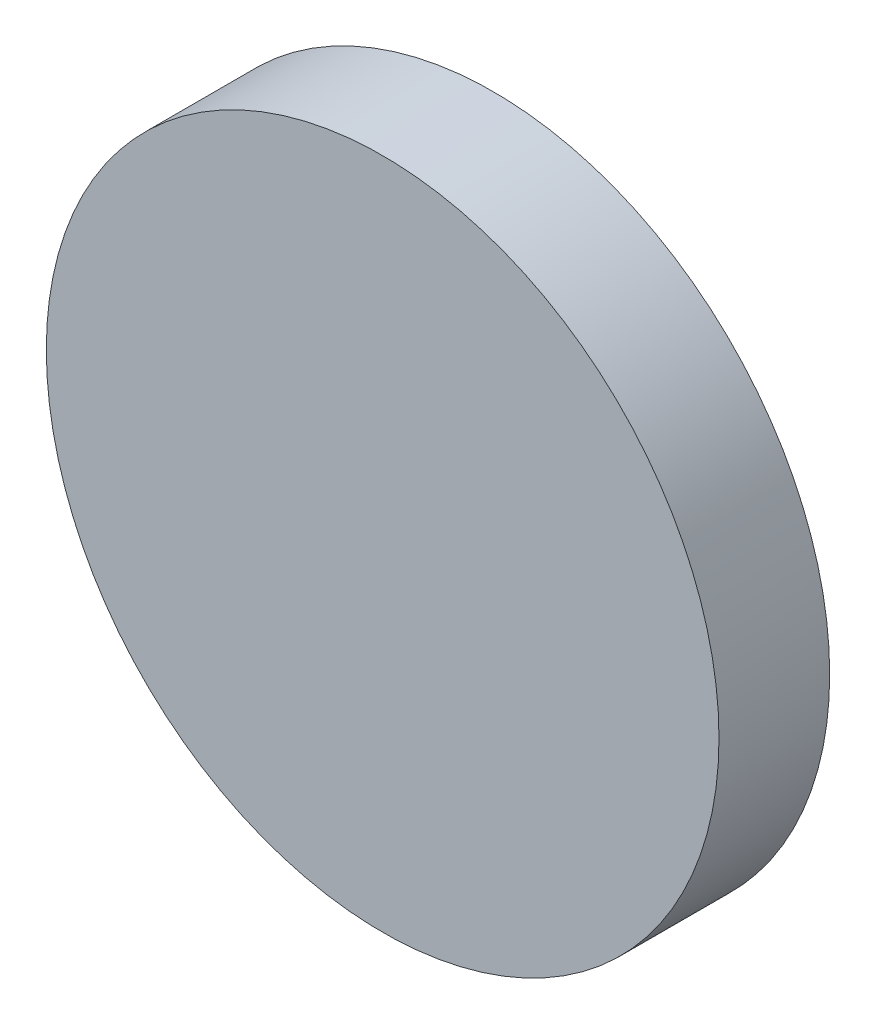
SolidWorks part; units mm, degrees
ref_plane "Front Plane" through (0, 0, 0) normal (0, 0, 1) x (1, 0, 0)
ref_plane "Top Plane" through (0, 0, 0) normal (0, 1, 0) x (1, 0, 0)
ref_plane "Right Plane" through (0, 0, 0) normal (1, 0, 0) x (0, 0, -1)
sketch "Sketch1" plane through (0, 0, 0) normal (0, 0, 1) x (1, 0, 0)
  circle A0 centre (0, 0) radius 39.5
extrude "Boss-Extrude1" add sketch "Sketch1" along normal blind 13 contours A0
